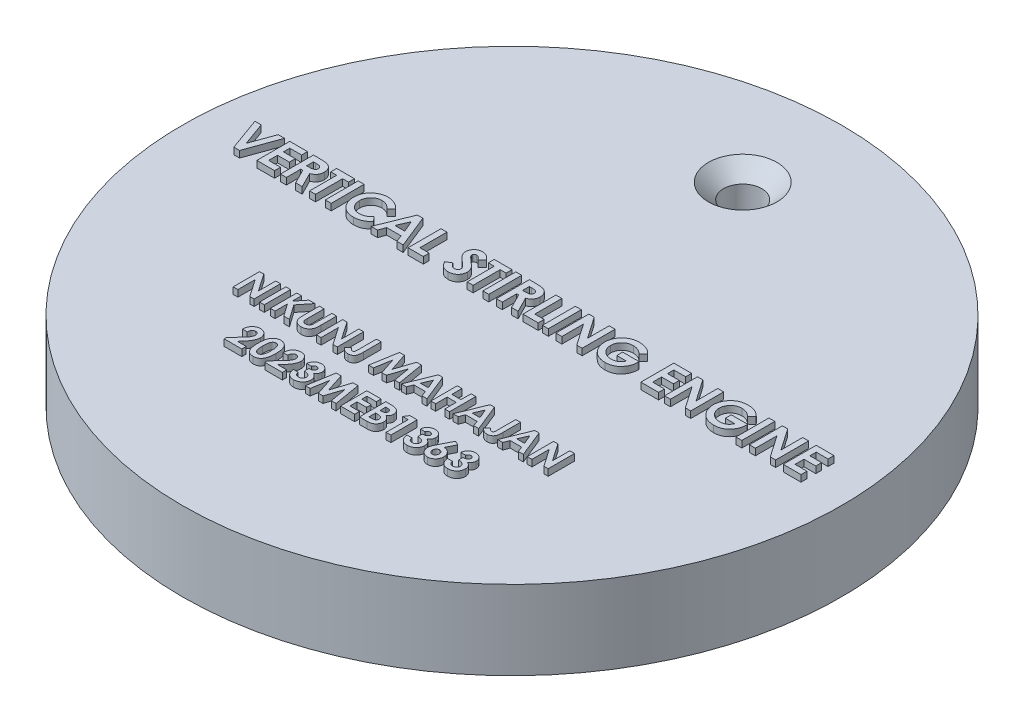
SolidWorks part; units mm, degrees
ref_plane "Front Plane" through (0, 0, 0) normal (0, 0, 1) x (1, 0, 0)
ref_plane "Top Plane" through (0, 0, 0) normal (0, 1, 0) x (1, 0, 0)
ref_plane "Right Plane" through (0, 0, 0) normal (1, 0, 0) x (0, 0, -1)
sketch "Sketch1" plane through (0, 0, 0) normal (0, 1, 0) x (1, 0, 0)
  circle A0 centre (0, 0) radius 50
  dimension "D1" = 100
extrude "Boss-Extrude1" add sketch "Sketch1" along normal blind 12
sketch "Sketch2" plane through (0, 12, 0) normal (0, 1, 0) x (1, 0, 0)
  line L0 (-50, 0) -> (50, 0) construction
  circle A0 centre (0, 0) radius 50 construction
  text T0 "VERTICAL STIRLING ENGINE" font "Century Gothic" height 5
extrude "Boss-Extrude2" add sketch "Sketch2" along normal blind 1
hole_wizard "CSK for M5 Flat Head Machine Screw1" positions "Sketch4" profile "Sketch5" countersink size "M5" standard "ANSI Metric" end condition through all
sketch "Sketch4" plane through (0, 12, 0) normal (0, 1, 0) x (1, 0, 0)
  point P0 (0, 35)
  point P2 (0, 35)
  dimension "D1" = 35
sketch "Sketch5" plane through (0, 12, -35) normal (1, 0, 0) x (0, 0, 1)
  line L0 (0, 0) -> (0, 12)
  line L1 (0, 12) -> (2.925, 12)
  line L2 (2.9, 11.975) -> (2.9, 2.3)
  line L3 (2.9, 2.3) -> (5.2, 0)
  line L5 (5.2, 0) -> (0, 0)
  line L6 (-2.9, 2.3) -> (-5.2, 0) construction
  line L7 (2.925, 12) -> (2.9, 11.975)
  line L8 (-2.925, 12) -> (-2.9, 11.975) construction
  line L11 (0, -6.35) -> (0, 107.95) construction
  dimension "Thru Hole Dia." = 5.8
  dimension "Thru Hole Depth" = 12
  dimension "Near C'Sink Dia." = 10.4
  dimension "Near C'Sink Angle" = 90
  dimension "Far C'Sink Dia." = 5.85
  dimension "Far C'Sink Angle" = 90
sketch "Sketch6" plane through (0, 0, 0) normal (0, 1, 0) x (1, 0, 0)
  line L0 (-46.489, -18.4058) -> (46.489, -18.4058) construction
  circle A0 centre (0, 0) radius 50 construction
  text T0 "NIKUNJ MAHAJAN\r\n2023MEB1363" font "Century Gothic" height 4
extrude "Boss-Extrude5" add sketch "Sketch6" along normal offset from surface (13 mm away) 1 up to face at (0, 12, -29.8) offset beyond the face yes
